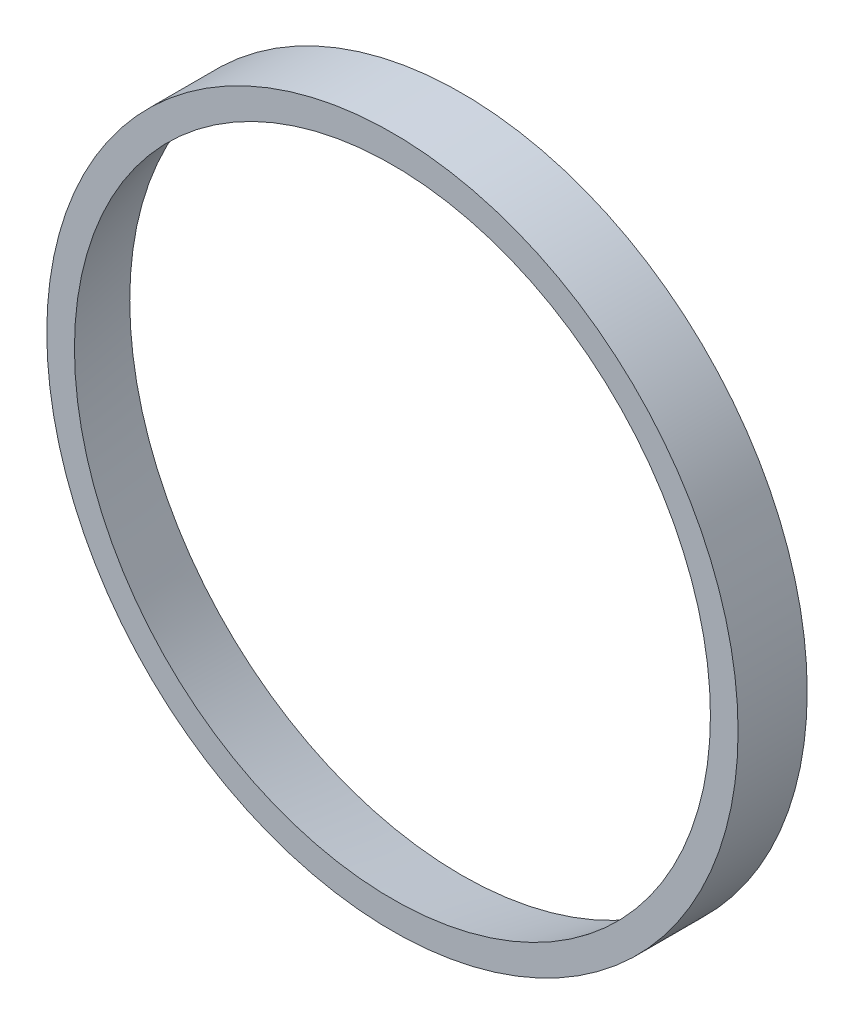
SolidWorks part; units mm, degrees
ref_plane "Front Plane" through (0, 0, 0) normal (0, 0, 1) x (1, 0, 0)
ref_plane "Top Plane" through (0, 0, 0) normal (0, 1, 0) x (1, 0, 0)
ref_plane "Right Plane" through (0, 0, 0) normal (1, 0, 0) x (0, 0, -1)
sketch "Sketch1" plane through (0, 0, 0) normal (0, 1, 0) x (1, 0, 0)
  line L0 (0, 0) -> (18.2584, 0) construction
  line L1 (15.875, 0) -> (15.875, 3.175)
  line L5 (0, 0) -> (0, 7.6066) construction
  line L6 (15.875, 3.175) -> (15.24, 3.175)
  line L7 (15.24, 3.175) -> (14.605, 0)
  line L8 (14.605, 0) -> (15.875, 0)
  dimension "D1" = 15.875
  dimension "D2" = 3.175
  dimension "D3" = 0.635
  dimension "D4" = 1.27
revolve "Revolve1" add sketch "Sketch1" angle 360 about L5
